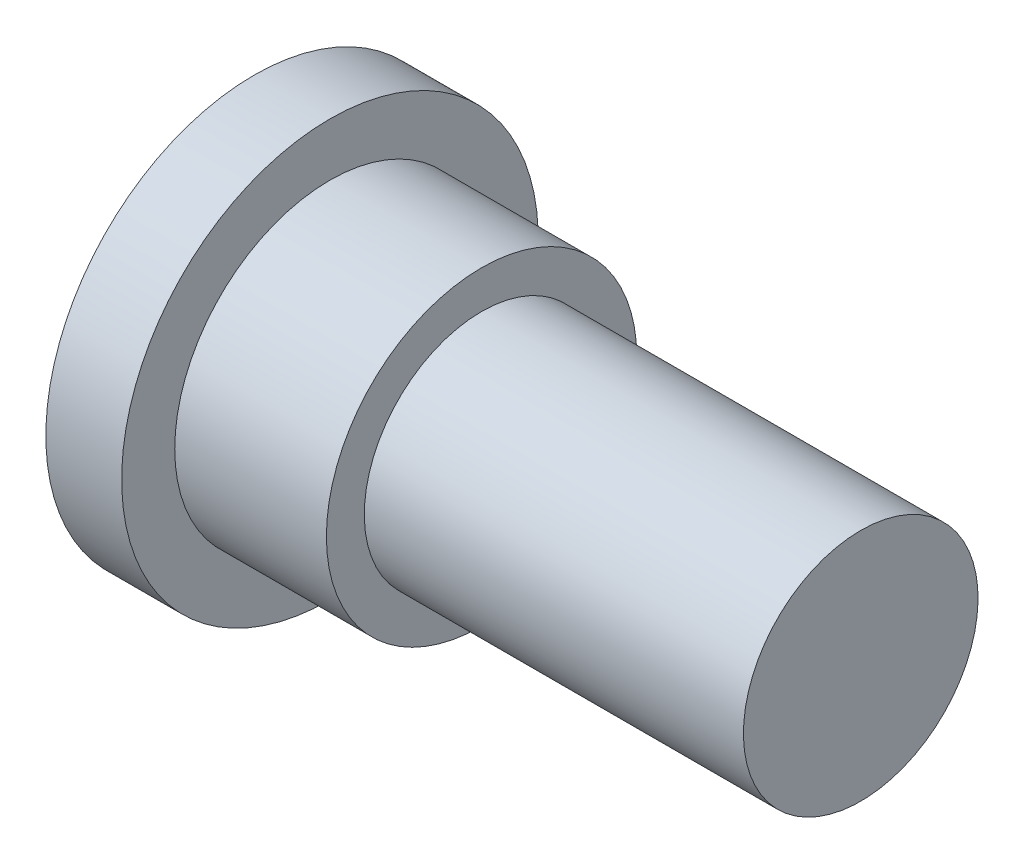
SolidWorks part; units mm, degrees
ref_plane "Front Plane" through (0, 0, 0) normal (0, 0, 1) x (1, 0, 0)
ref_plane "Top Plane" through (0, 0, 0) normal (0, 1, 0) x (1, 0, 0)
ref_plane "Right Plane" through (0, 0, 0) normal (1, 0, 0) x (0, 0, -1)
sketch "Sketch1" plane through (0, 0, 0) normal (0, 0, 1) x (1, 0, 0)
  line L0 (0, 0) -> (0, 27.4706)
  line L1 (0, 27.4706) -> (10, 27.4706)
  line L2 (10, 27.4706) -> (10, 20.4706)
  line L3 (10, 20.4706) -> (30, 20.4706)
  line L4 (30, 20.4706) -> (30, 15.4706)
  line L5 (30, 15.4706) -> (80, 15.4706)
  line L6 (80, 15.4706) -> (80, 0)
  line L7 (80, 0) -> (0, 0)
  dimension "D1" = 15.4706
  dimension "D2" = 5
  dimension "D3" = 7
  dimension "D4" = 50
  dimension "D5" = 20
  dimension "D6" = 10
revolve "Revolve1" add sketch "Sketch1" angle 360 about L7
sketch "Sketch2" plane through (0, 0, 0) normal (0, 0, 1) x (1, 0, 0)
  line L0 (80, 0) -> (-20, 0) construction
  line L1 (80, -15.4706) -> (80, 15.4706) construction
  dimension "D1" = 100
